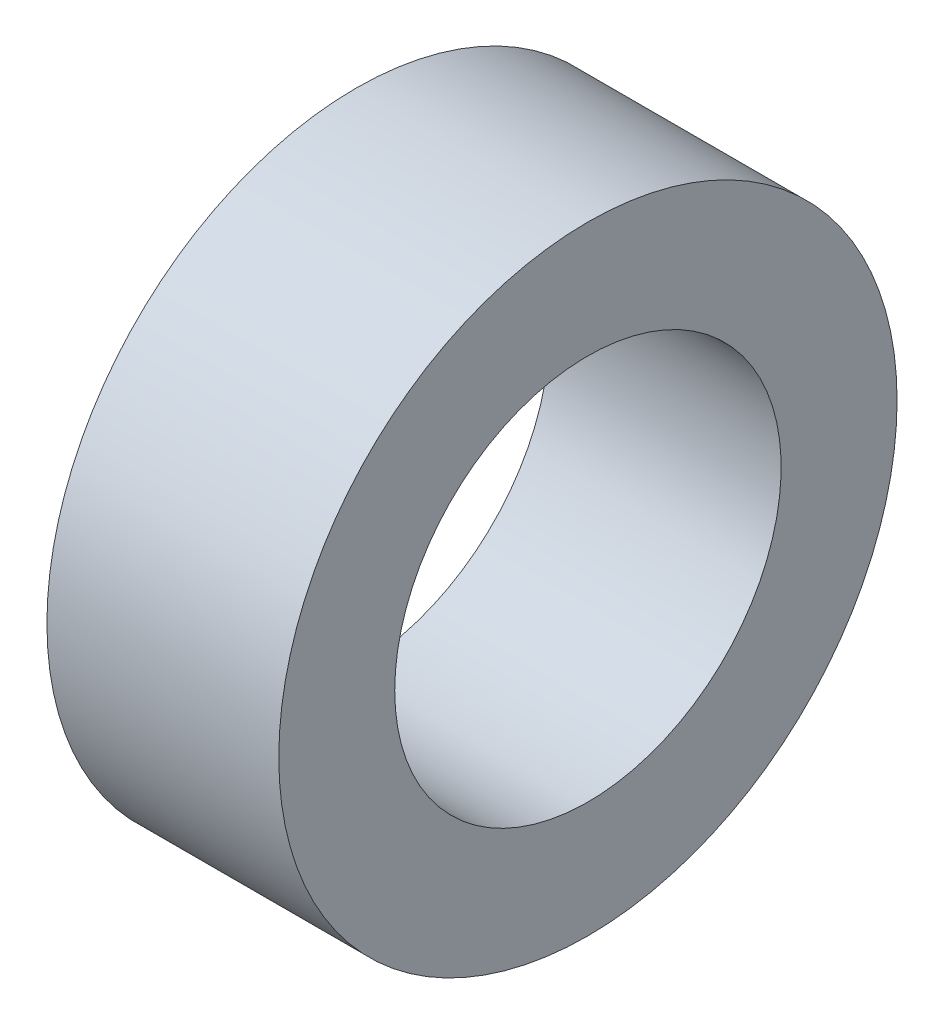
SolidWorks part; units mm, degrees
material "PA Type 6"
ref_plane "Front Plane" through (0, 0, 0) normal (0, 0, 1) x (1, 0, 0)
ref_plane "Top Plane" through (0, 0, 0) normal (0, 1, 0) x (1, 0, 0)
ref_plane "Right Plane" through (0, 0, 0) normal (1, 0, 0) x (0, 0, -1)
sketch "Sketch1" plane through (0, 0, 0) normal (0, 0, 1) x (1, 0, 0)
  line L0 (0, 0) -> (6, 0) construction
  line L1 (0, 5) -> (6, 5)
  line L2 (0, 5) -> (0, 8)
  line L3 (0, 8) -> (6, 8)
  line L4 (6, 5) -> (6, 8)
  dimension "D1" = 5
  dimension "D2" = 8
  dimension "D3" = 6
revolve "Revolve1" add sketch "Sketch1" angle 360 about L0
